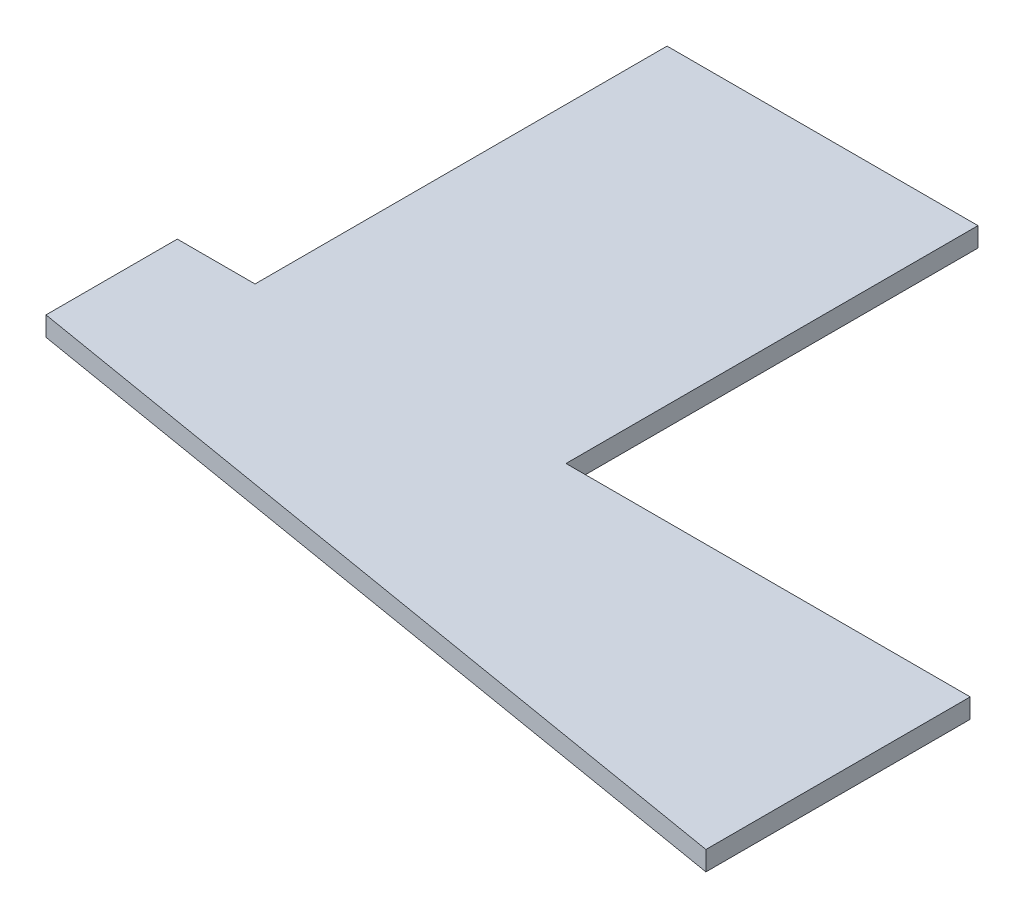
SolidWorks part; units mm, degrees
ref_plane "Front Plane" through (0, 0, 0) normal (0, 0, 1) x (1, 0, 0)
ref_plane "Top Plane" through (0, 0, 0) normal (0, 1, 0) x (1, 0, 0)
ref_plane "Right Plane" through (0, 0, 0) normal (1, 0, 0) x (0, 0, -1)
sketch "Sketch2" plane through (0, 0, 0) normal (0, 1, 0) x (1, 0, 0)
  line L0 (50.8, 0) -> (116.84, 0)
  line L2 (0, 0) -> (0, 67.31)
  line L3 (0, 67.31) -> (50.8, 67.31)
  line L4 (50.8, 0) -> (50.8, 67.31)
  line L5 (-55, 0) -> (55, 0) construction
  line L7 (116.84, -43.18) -> (-12.7, -21.4492)
  line L8 (-12.7, -21.4492) -> (-12.7, 0)
  line L9 (-12.7, 0) -> (0, 0)
  line L11 (116.84, -43.18) -> (116.84, 0)
  point P5 (-12.7, -21.4492)
  point P12 (116.84, -42.8041)
  point P13 (116.84, -0.6959)
  dimension "D1" = 50.8
  dimension "D2" = 67.31
  dimension "D3" = 66.04
  dimension "D4" = 12.7
  dimension "D5" = 43.18
extrude "Boss-Extrude1" add sketch "Sketch2" along normal blind 3.175
